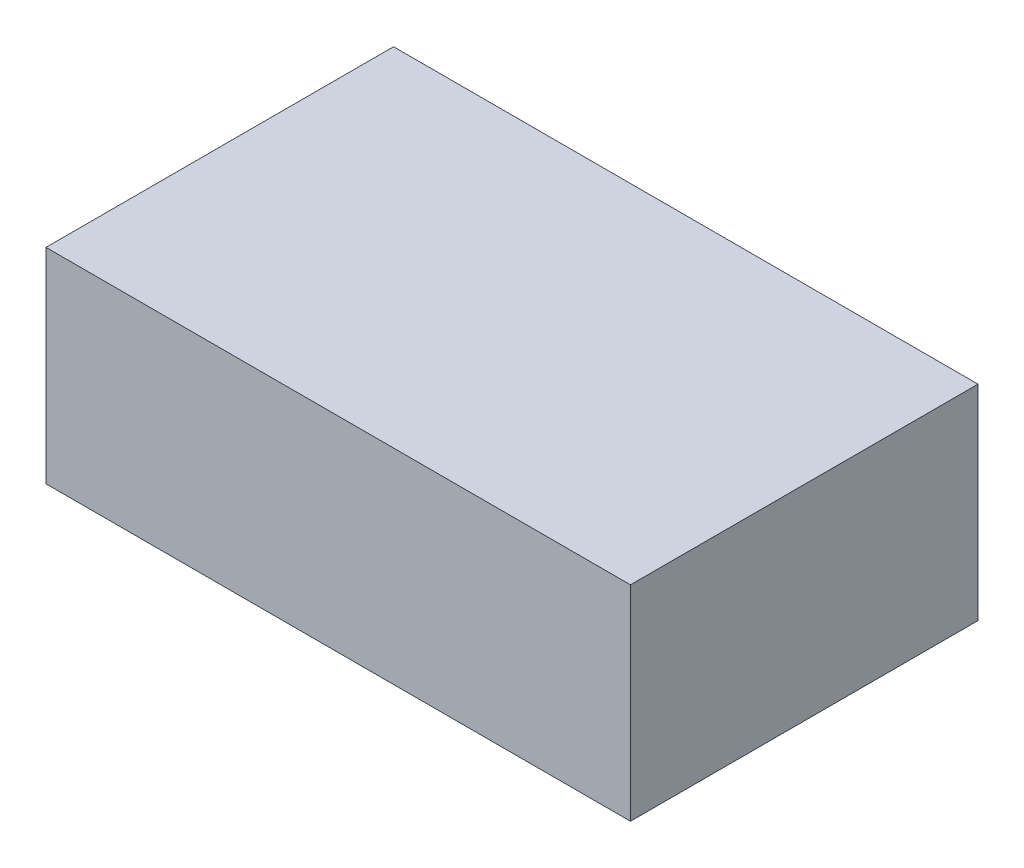
SolidWorks part; units mm, degrees
ref_plane "Front Plane" through (0, 0, 0) normal (0, 0, 1) x (1, 0, 0)
ref_plane "Top Plane" through (0, 0, 0) normal (0, 1, 0) x (1, 0, 0)
ref_plane "Right Plane" through (0, 0, 0) normal (1, 0, 0) x (0, 0, -1)
sketch "Sketch1" plane through (0, 0, 0) normal (0, 0, 1) x (1, 0, 0)
  line L0 (-1.37, -1.37) -> (6.45, -1.37)
  line L1 (6.45, -1.37) -> (6.45, 1.37)
  line L2 (6.45, 1.37) -> (-1.37, 1.37)
  line L3 (-1.37, 1.37) -> (-1.37, -1.37)
extrude "Component_Outline" add sketch "Sketch1" along normal blind 4.65 separate body
sketch3d "3DSketch1"
  line L0 (0, 0, 0) -> (1, 0, 0)
  line L1 (0, 0, 0) -> (0, 1, 0)
  line L2 (0, 0, 0) -> (0, 0, 1)
  point P0 (0, 0, 0)
